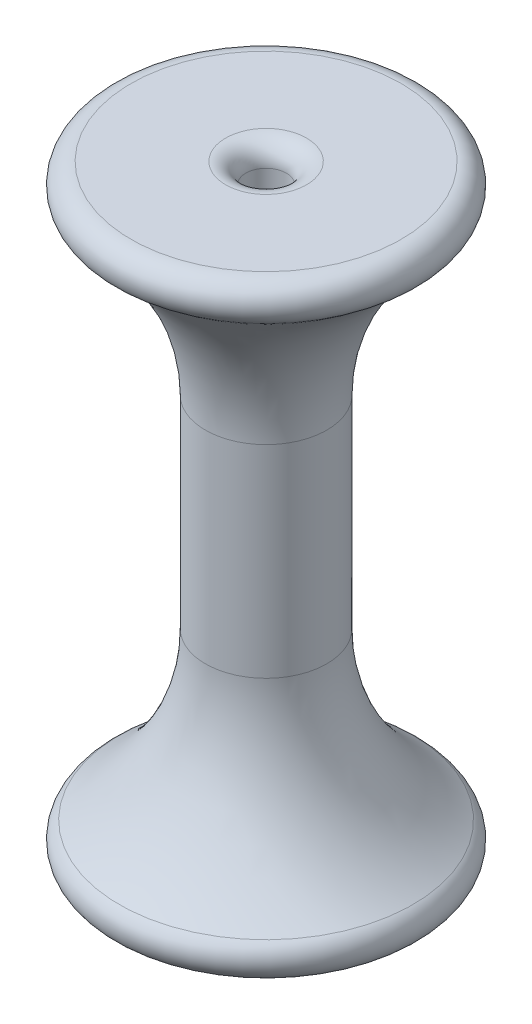
SolidWorks part; units mm, degrees
ref_plane "前视基准面" through (0, 0, 0) normal (0, 0, 1) x (1, 0, 0)
ref_plane "上视基准面" through (0, 0, 0) normal (0, 1, 0) x (1, 0, 0)
ref_plane "右视基准面" through (0, 0, 0) normal (1, 0, 0) x (0, 0, -1)
sketch "草图1" plane through (0, 0, 0) normal (0, 0, 1) x (1, 0, 0)
  line L0 (-13, 5) -> (-13, -5) construction
  line L1 (-3, 5) -> (-3, -5)
  line L2 (-13, 15) -> (0, 15)
  line L3 (-13, -15) -> (0, -15)
  line L4 (0, -15) -> (0, 0)
  line L5 (0, 0) -> (0, 15)
  circle A0 centre (-13, -5) radius 10
  circle A1 centre (-13, 5) radius 10
  point P4 (-13, 0)
  dimension "D1" = 20
  dimension "D2" = 10
  dimension "D3" = 3
  dimension "D4" = 13
sketch "草图4" plane through (0, 0, 0) normal (0, 0, 1) x (1, 0, 0)
  line L0 (-13, 15) -> (0, 15) construction
  line L1 (-13, -15) -> (0, -15) construction
  line L2 (0, -15) -> (0, 0) construction
  line L3 (0, 0) -> (0, 15) construction
  line L4 (-6.6754, 15) -> (-2, 15)
  line L5 (-6.6754, -15) -> (-2, -15)
  line L6 (0, -15) -> (0, 0) construction
  line L7 (0, 0) -> (0, 15) construction
  line L8 (-3, 5) -> (-3, -5) construction
  line L9 (-3, 5) -> (-3, -5)
  line L10 (-1, 14) -> (-1, -14)
  arc A0 (-3, 5) -> (-7.2504, 13.1818) centre (-13, 5) ccw
  arc A1 (-3, -5) -> (-7.2504, -13.1818) centre (-13, -5) cw
  arc A2 (-6.6754, 15) -> (-7.2504, 13.1818) centre (-6.6754, 14) ccw
  arc A3 (-7.2504, -13.1818) -> (-6.6754, -15) centre (-6.6754, -14) ccw
  arc A4 (-1, 14) -> (-2, 15) centre (-2, 14) ccw
  arc A5 (-2, -15) -> (-1, -14) centre (-2, -14) ccw
  point P23 (-3.7432, -13.1818)
  dimension "D2" = 2
  dimension "D3" = 1
  dimension "D4" = 2
  dimension "D5" = 2
  dimension "D1" = 1
revolve "旋转1" add sketch "草图4" angle 360 about L5
